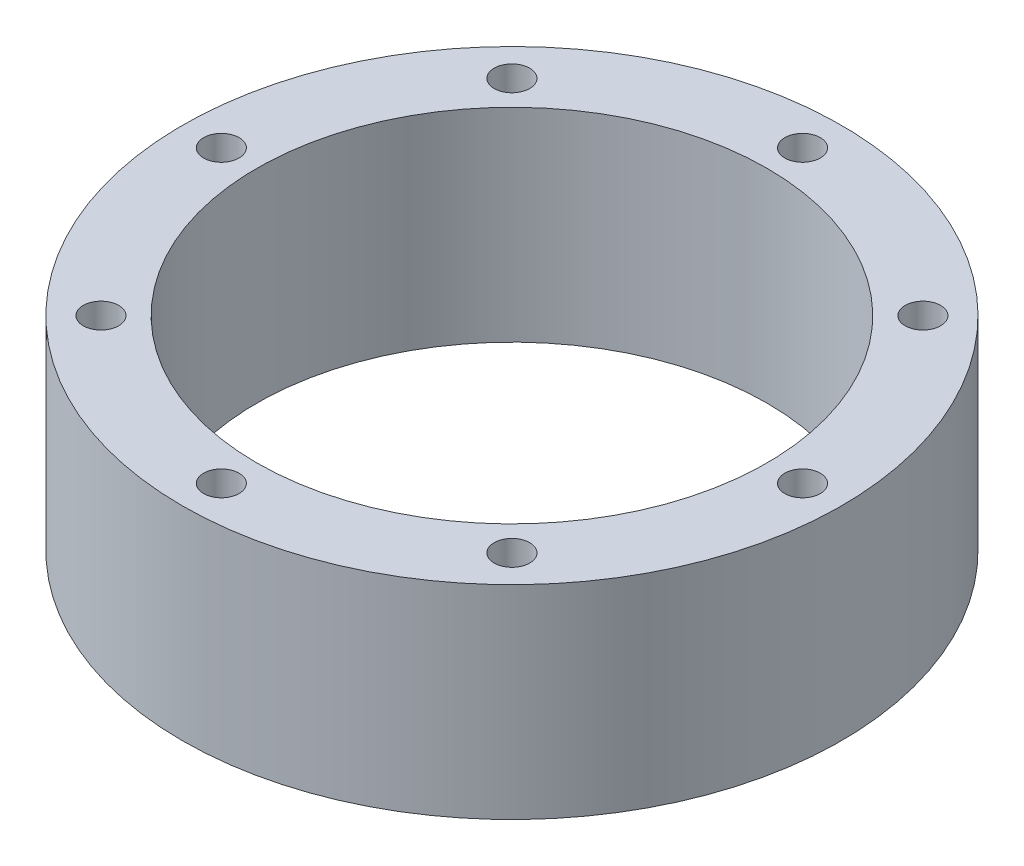
SolidWorks part; units mm, degrees
ref_plane "Front Plane" through (0, 0, 0) normal (0, 0, 1) x (1, 0, 0)
ref_plane "Top Plane" through (0, 0, 0) normal (0, 1, 0) x (1, 0, 0)
ref_plane "Right Plane" through (0, 0, 0) normal (1, 0, 0) x (0, 0, -1)
sketch "Sketch1" plane through (0, 0, 0) normal (0, 1, 0) x (1, 0, 0)
  circle A0 centre (0, 0) radius 46.5
  circle A1 centre (0, 0) radius 36
  dimension "D1" = 93
  dimension "D2" = 72
extrude "Boss-Extrude1" add sketch "Sketch1" along normal blind 28.7
sketch "Sketch2" plane through (0, 28.7, 0) normal (0, 1, 0) x (1, 0, 0)
  circle A0 centre (0, 0) radius 41 construction
  circle A1 centre (0, 41) radius 2.5
  circle A2 centre (28.9914, 28.9914) radius 2.5
  circle A3 centre (41, 0) radius 2.5
  circle A4 centre (28.9914, -28.9914) radius 2.5
  circle A5 centre (0, -41) radius 2.5
  circle A6 centre (-28.9914, -28.9914) radius 2.5
  circle A7 centre (-41, 0) radius 2.5
  circle A8 centre (-28.9914, 28.9914) radius 2.5
  point P5 (0, 0)
  point P6 (0, 0)
  point P22 (0, 0)
  dimension "D1" = 82
  dimension "D2" = 5
  dimension "D3" = 8
extrude "Cut-Extrude1" cut sketch "Sketch2" against normal through all
